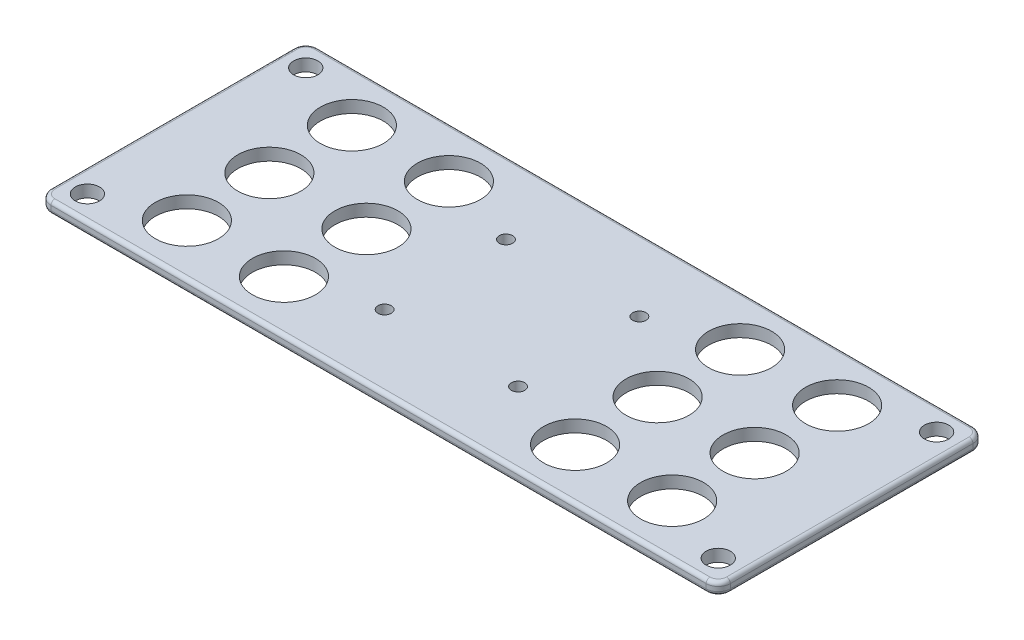
SolidWorks part; units mm, degrees
ref_plane "Front Plane" through (0, 0, 0) normal (0, 0, 1) x (1, 0, 0)
ref_plane "Top Plane" through (0, 0, 0) normal (0, 1, 0) x (1, 0, 0)
ref_plane "Right Plane" through (0, 0, 0) normal (1, 0, 0) x (0, 0, -1)
sketch "Sketch1" plane through (0, 0, 0) normal (0, 1, 0) x (1, 0, 0)
  line L1 (-88.9, -34.925) -> (88.9, -34.925)
  line L2 (-88.9, -34.925) -> (-88.9, 34.925)
  line L3 (-88.9, 34.925) -> (88.9, 34.925)
  line L4 (88.9, -34.925) -> (88.9, 34.925)
  line L5 (-88.9, -34.925) -> (88.9, 34.925) construction
  line L6 (-88.9, 34.925) -> (88.9, -34.925) construction
  point P0 (0, 0)
  dimension "D1" = 69.85
  dimension "D2" = 177.8
extrude "Boss-Extrude1" add sketch "Sketch1" along normal blind 3.175
sketch "Sketch2" plane through (0, 3.175, 0) normal (0, 1, 0) x (1, 0, 0)
  line L0 (-88.9, 34.925) -> (-88.9, -34.925) construction
  line L1 (-82.55, -28.575) -> (82.55, -28.575) construction
  line L2 (-82.55, -28.575) -> (-82.55, 28.575) construction
  line L3 (-82.55, 28.575) -> (82.55, 28.575) construction
  line L4 (82.55, -28.575) -> (82.55, 28.575) construction
  line L5 (-82.55, -28.575) -> (82.55, 28.575) construction
  line L6 (-82.55, 28.575) -> (82.55, -28.575) construction
  line L7 (88.9, 34.925) -> (-88.9, 34.925) construction
  circle A0 centre (-82.55, 28.575) radius 3.175
  circle A1 centre (-82.55, -28.575) radius 3.175
  circle A2 centre (82.55, 28.575) radius 3.175
  circle A3 centre (82.55, -28.575) radius 3.175
  point P0 (0, 0)
  dimension "D1" = 6.35
  dimension "D2" = 6.35
  dimension "D3" = 6.35
  dimension "D4" = 6.35
  dimension "D5" = 6.35
  dimension "D6" = 6.35
extrude "Cut-Extrude1" cut sketch "Sketch2" against normal through all
fillet "Fillet1" radius 3.175 4 edges at (88.9, 1.5875, -34.925) (88.9, 1.5875, 34.925) (-88.9, 1.5875, -34.925) (-88.9, 1.5875, 34.925)
fillet "Fillet2" radius 1 16 edges at (-87.9701, 0, 33.9951) (-88.9, 0, 0) (-87.9701, 0, -33.9951) (0, 0, -34.925) (87.9701, 0, -33.9951) (88.9, 0, 0) (87.9701, 0, 33.9951) (-87.9701, 3.175, 33.9951) (-88.9, 3.175, 0) (-87.9701, 3.175, -33.9951) (0, 3.175, -34.925) (87.9701, 3.175, -33.9951) (88.9, 3.175, 0) (87.9701, 3.175, 33.9951) (0, 0, 34.925) (0, 3.175, 34.925)
sketch "Sketch3" plane through (0, 3.175, 0) normal (0, 1, 0) x (1, 0, 0)
  line L0 (0, 33.925) -> (0, -33.925) construction
  line L1 (85.725, 33.925) -> (-85.725, 33.925) construction
  line L2 (-85.725, -33.925) -> (85.725, -33.925) construction
  line L3 (-63.5, 33.925) -> (-63.5, -33.925) construction
  line L4 (-17.4625, -15.875) -> (17.4625, -15.875) construction
  line L5 (-17.4625, -15.875) -> (-17.4625, 15.875) construction
  line L6 (-17.4625, 15.875) -> (17.4625, 15.875) construction
  line L7 (17.4625, -15.875) -> (17.4625, 15.875) construction
  line L8 (-17.4625, -15.875) -> (17.4625, 15.875) construction
  line L9 (-17.4625, 15.875) -> (17.4625, -15.875) construction
  line L10 (-38.1, 33.925) -> (-38.1, -33.925) construction
  line L11 (63.5, 33.925) -> (63.5, -33.925) construction
  line L12 (38.1, 33.925) -> (38.1, -33.925) construction
  line L13 (-63.5, -21.59) -> (63.5, -21.59) construction
  line L14 (-63.5, 21.59) -> (63.5, 21.59) construction
  circle A0 centre (17.4625, 15.875) radius 1.7462
  circle A1 centre (17.4625, -15.875) radius 1.7462
  circle A2 centre (-17.4625, -15.875) radius 1.7462
  circle A3 centre (-17.4625, 15.875) radius 1.7462
  circle A5 centre (-63.5, 21.59) radius 8.255
  circle A6 centre (-38.1, 21.59) radius 8.255
  circle A7 centre (-38.1, 0) radius 8.255
  circle A8 centre (-63.5, 0) radius 8.255
  circle A9 centre (-38.1, -21.59) radius 8.255
  circle A10 centre (-63.5, -21.59) radius 8.255
  circle A11 centre (38.1, -21.59) radius 8.255
  circle A12 centre (63.5, -21.59) radius 8.255
  circle A13 centre (38.1, 0) radius 8.255
  circle A14 centre (63.5, 0) radius 8.255
  circle A15 centre (38.1, 21.59) radius 8.255
  circle A16 centre (63.5, 21.59) radius 8.255
  point P6 (0, 0)
  dimension "D3" = 3.4925
  dimension "D4" = 3.4925
  dimension "D5" = 3.4925
  dimension "D6" = 3.4925
  dimension "D13" = 16.51
  dimension "D1" = 34.925
  dimension "D2" = 31.75
  dimension "D7" = 21.59
  dimension "D8" = 21.59
  dimension "D9" = 38.1
  dimension "D10" = 38.1
  dimension "D11" = 25.4
  dimension "D12" = 25.4
extrude "Cut-Extrude2" cut sketch "Sketch3" against normal through all
